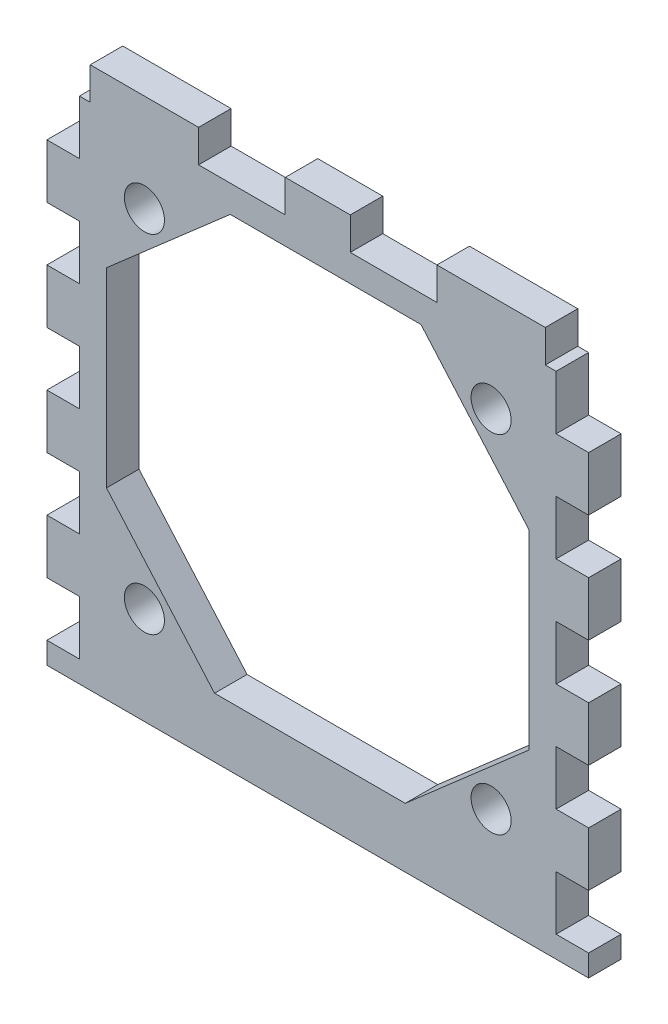
SolidWorks part; units mm, degrees
material "Beech"
ref_plane "Front Plane" through (0, 0, 0) normal (0, 0, 1) x (1, 0, 0)
ref_plane "Top Plane" through (0, 0, 0) normal (0, 1, 0) x (1, 0, 0)
ref_plane "Right Plane" through (0, 0, 0) normal (1, 0, 0) x (0, 0, -1)
sketch "Sketch1" plane through (0, 0, 0) normal (0, 0, 1) x (1, 0, 0)
  line L0 (4, 50) -> (4, 47)
  line L1 (0, 0) -> (50, 0)
  line L2 (0, 0) -> (0, 50)
  line L3 (0, 50) -> (50, 50)
  line L4 (50, 0) -> (50, 50)
  line L5 (4, 47) -> (14, 47)
  line L6 (14, 47) -> (14, 50)
  line L7 (22, 50) -> (22, 47)
  line L8 (22, 47) -> (28, 47)
  line L9 (28, 47) -> (28, 50)
  line L10 (36, 50) -> (36, 47)
  line L11 (36, 47) -> (46, 47)
  line L12 (46, 47) -> (46, 50)
  line L13 (4, 47) -> (0, 47)
  line L14 (14, 47) -> (22, 47)
  line L15 (28, 47) -> (36, 47)
  line L16 (46, 47) -> (50, 47)
  line L17 (50, 47) -> (47, 47)
  line L18 (47, 47) -> (47, 42)
  line L19 (47, 42) -> (50, 42)
  line L20 (50, 37) -> (47, 37)
  line L21 (47, 32) -> (50, 32)
  line L22 (47, 37) -> (47, 32)
  line L23 (50, 27) -> (47, 27)
  line L24 (47, 22) -> (50, 22)
  line L25 (47, 27) -> (47, 22)
  line L26 (50, 17) -> (47, 17)
  line L27 (47, 12) -> (50, 12)
  line L28 (47, 17) -> (47, 12)
  line L29 (50, 7) -> (47, 7)
  line L30 (47, 2) -> (50, 2)
  line L31 (47, 7) -> (47, 2)
  line L32 (0, 47) -> (3, 47)
  line L33 (3, 47) -> (3, 42)
  line L34 (3, 42) -> (0, 42)
  line L35 (0, 37) -> (3, 37)
  line L36 (3, 37) -> (3, 32)
  line L37 (3, 32) -> (0, 32)
  line L38 (0, 27) -> (3, 27)
  line L39 (3, 27) -> (3, 22)
  line L40 (3, 22) -> (0, 22)
  line L41 (0, 17) -> (3, 17)
  line L42 (3, 17) -> (3, 12)
  line L43 (3, 12) -> (0, 12)
  line L44 (0, 7) -> (3, 7)
  line L45 (3, 7) -> (3, 2)
  line L46 (3, 2) -> (0, 2)
  point P11 (14, 48.5)
  point P18 (28, 48.5)
  dimension "D1" = 50
  dimension "D2" = 50
  dimension "D3" = 10
  dimension "D4" = 8
  dimension "D5" = 6
  dimension "D6" = 8
  dimension "D7" = 10
  dimension "D8" = 4
  dimension "D9" = 3
  dimension "D10" = 3
  dimension "D11" = 5
  dimension "D12" = 3
  dimension "D14" = 3
  dimension "D16" = 5
  dimension "D13" = 5
  dimension "D15" = 5
extrude "Boss-Extrude1" add sketch "Sketch1" along normal blind 3 contours L44 L45 L1 L31 L29 L4 L27 L28 L26 L24 L25 L23 L21 L22 L20 L19 L18 L17 L16 L11 L15 L8 L14 L5 L13 L2 L32 L33 L34 L35 L36 L37 L38 L39 L40 L41 L42 L43 | L5 L6 L3 L0 | L8 L9 L3 L7 | L11 L12 L3 L10
sketch "Sketch2" plane through (0, 0, 0) normal (0, 0, 1) x (1, 0, 0)
  line L0 (33.075, 5.5) -> (15.475, 5.5)
  line L1 (5.2503, 0) -> (44.7497, 0)
  line L2 (0, 5.2503) -> (0, 44.7497)
  line L3 (5.2503, 50) -> (44.7497, 50)
  line L4 (50, 5.2503) -> (50, 44.7497)
  line L5 (15.475, 5.5) -> (5.5, 16.925)
  line L6 (5.5, 16.925) -> (5.5, 34.525)
  line L7 (5.5, 34.525) -> (16.925, 44.5)
  line L8 (16.925, 44.5) -> (34.525, 44.5)
  line L9 (34.525, 44.5) -> (44.5, 33.075)
  line L10 (44.5, 33.075) -> (44.5, 15.475)
  line L11 (44.5, 15.475) -> (33.075, 5.5)
  circle A0 centre (9, 41) radius 1.85
  circle A1 centre (41, 41) radius 1.85
  circle A2 centre (41, 9) radius 1.85
  circle A3 centre (9, 9) radius 1.85
  arc A4 (44.7497, 50) -> (50, 44.7497) centre (44.7497, 44.7497) cw
  arc A5 (50, 5.2503) -> (44.7497, 0) centre (44.7497, 5.2503) cw
  arc A6 (5.2503, 0) -> (0, 5.2503) centre (5.2503, 5.2503) cw
  arc A7 (0, 44.7497) -> (5.2503, 50) centre (5.2503, 44.7497) cw
  point P23 (50, 50)
  point P28 (0, 0)
  point P31 (0, 50)
  dimension "D5" = 3.7
  dimension "D6" = 3.7
  dimension "D7" = 3.7
  dimension "D8" = 3.7
  dimension "D21" = 5.2503
  dimension "D1" = 50
  dimension "D2" = 50
  dimension "D3" = 32
  dimension "D4" = 32
  dimension "D9" = 9
  dimension "D10" = 9
  dimension "D11" = 17.6
  dimension "D12" = 17.6
  dimension "D13" = 17.6
  dimension "D14" = 17.6
  dimension "D15" = 40
  dimension "D16" = 40
  dimension "D17" = 39
  dimension "D18" = 39
  dimension "D19" = 5.5
  dimension "D20" = 5.5
extrude "Cut-Extrude1" cut sketch "Sketch2" along normal through all contours A0 | A1 | A2 | A3 | L0 L5 L6 L7 L8 L9 L10 L11
